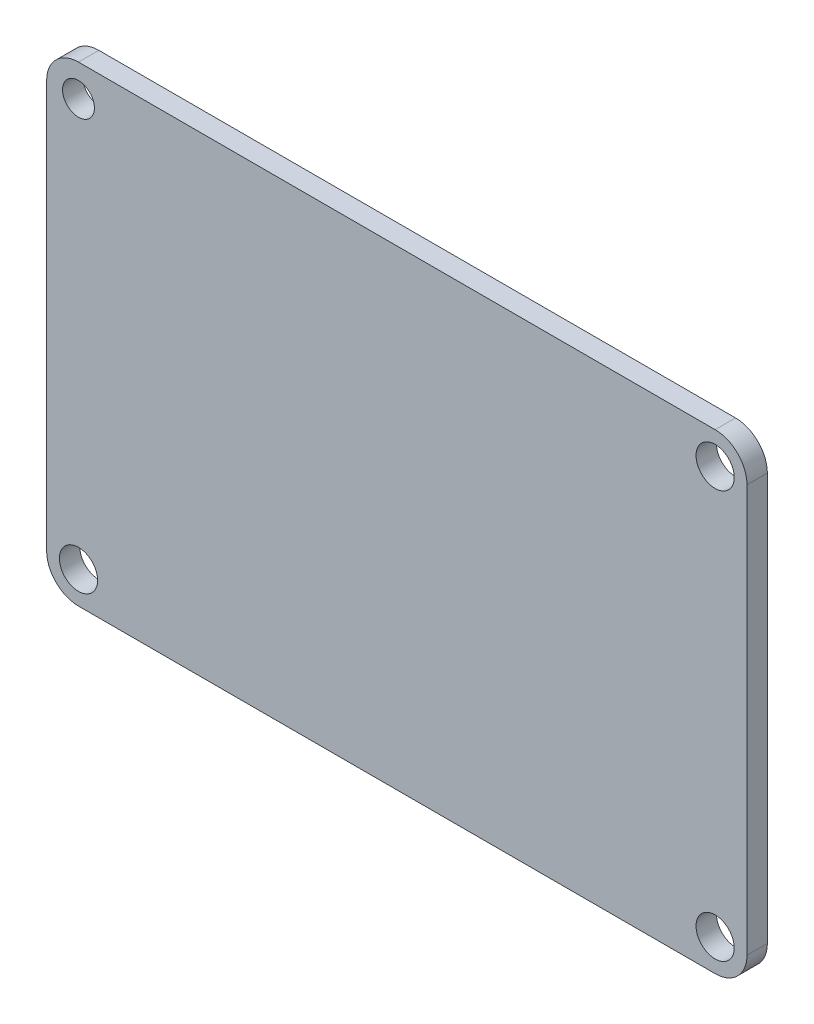
SolidWorks part; units mm, degrees
ref_plane "前视基准面" through (0, 0, 0) normal (0, 0, 1) x (1, 0, 0)
ref_plane "上视基准面" through (0, 0, 0) normal (0, 1, 0) x (1, 0, 0)
ref_plane "右视基准面" through (0, 0, 0) normal (1, 0, 0) x (0, 0, -1)
other "Configuration Table"
sketch "草图1" plane through (0, 0, 0) normal (0, 0, 1) x (1, 0, 0)
  line L1 (-27.5, -18.5) -> (27.5, -18.5)
  line L2 (-27.5, -18.5) -> (-27.5, 18.5)
  line L3 (-27.5, 18.5) -> (27.5, 18.5)
  line L4 (27.5, -18.5) -> (27.5, 18.5)
  line L5 (-27.5, -18.5) -> (27.5, 18.5) construction
  line L6 (-27.5, 18.5) -> (27.5, -18.5) construction
  point P0 (0, 0)
  dimension "D1" = 55
  dimension "D2" = 37
extrude "凸台-拉伸1" add sketch "草图1" along normal blind 1.6
sketch "草图3" plane through (0, 0, 0) normal (0, 0, 1) x (1, 0, 0)
  line L0 (-1000, 0) -> (49000, 0) construction
  line L1 (0, -1000) -> (0, 49000) construction
  line L2 (-25, 18.5) -> (-27.5, 18.5)
  line L3 (27.5, 16) -> (27.5, 18.5)
  line L4 (27.5, -18.5) -> (27.5, 18.5)
  line L5 (27.5, 18.5) -> (-27.5, 18.5)
  line L6 (-27.5, 18.5) -> (-27.5, -18.5)
  line L7 (-27.5, -18.5) -> (27.5, -18.5)
  line L8 (27.5, -18.5) -> (27.5, -16)
  line L9 (27.5, 18.5) -> (25, 18.5)
  line L10 (-27.5, 18.5) -> (-27.5, 16)
  line L11 (-27.5, -18.5) -> (-25, -18.5)
  line L12 (25, -18.5) -> (27.5, -18.5)
  line L13 (-27.5, -16) -> (-27.5, -18.5)
  arc A0 (-25, 18.5) -> (-27.5, 16) centre (-25, 16) ccw
  arc A1 (-27.5, -16) -> (-25, -18.5) centre (-25, -16) ccw
  arc A2 (27.5, -16) -> (25, -18.5) centre (25, -16) cw
  arc A3 (25, 18.5) -> (27.5, 16) centre (25, 16) cw
  dimension "D2" = 5
  dimension "D3" = 5
  dimension "D1" = 0
extrude "切除-拉伸1" cut sketch "草图3" along normal up to surface (1.6 mm away) from surface at 0 up to face at (0, 0, 1.6) starting at face at (0, 0, 0)
sketch "草图5" plane through (0, 0, 0) normal (0, 0, 1) x (1, 0, 0)
  circle A0 centre (-25, 16) radius 1.2504
  circle A1 centre (-25, -16) radius 1.5
  circle A2 centre (25, 16) radius 1.5
  circle A3 centre (25, -16) radius 1.5
  dimension "D1" = 2.5007
  dimension "D2" = 3
  dimension "D3" = 3
  dimension "D4" = 3
extrude "切除-拉伸2" cut sketch "草图5" along normal up to surface (1.6 mm away) from surface at 0 up to face at (0, 0, 1.6) starting at face at (0, 0, 0)
